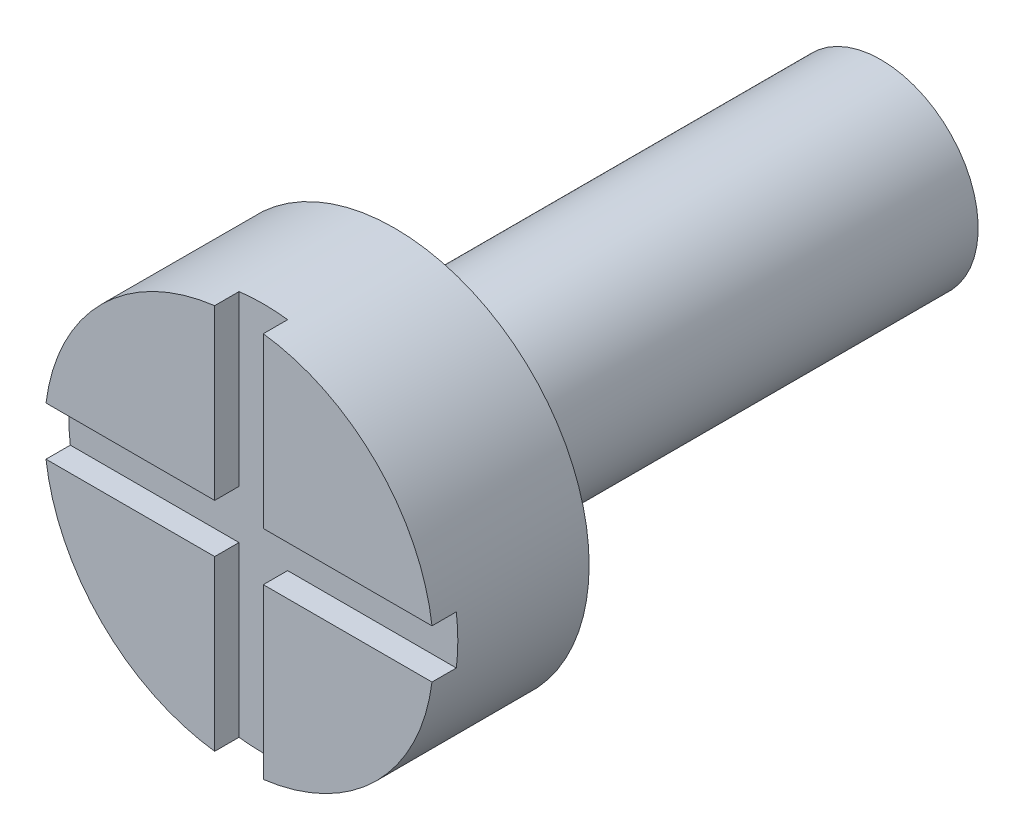
SolidWorks part; units mm, degrees
material "6061 Alloy"
ref_plane "Front Plane" through (0, 0, 0) normal (0, 0, 1) x (1, 0, 0)
ref_plane "Top Plane" through (0, 0, 0) normal (0, 1, 0) x (1, 0, 0)
ref_plane "Right Plane" through (0, 0, 0) normal (1, 0, 0) x (0, 0, -1)
sketch "Sketch1" plane through (0, 0, 0) normal (1, 0, 0) x (0, 0, -1)
  line L0 (0, 1) -> (0, 2)
  line L1 (0, 0) -> (5, 0) construction
  line L2 (5, 0) -> (5, 1)
  line L3 (5, 1) -> (0, 1)
  line L4 (0, 0) -> (-1.6, 0) construction
  line L5 (0, 2) -> (-1.6, 2)
  line L6 (-1.6, 2) -> (-1.6, 0)
  line L7 (5, 0) -> (-1.6, 0)
  dimension "D1" = 2
  dimension "D2" = 5
  dimension "D3" = 1
  dimension "D4" = 1.6
  dimension "D5" = 1.6
revolve "Revolve1" add sketch "Sketch1" angle 360 about L7
sketch "Sketch2" plane through (0, 0, 1.6) normal (0, 0, 1) x (1, 0, 0)
  line L0 (0, 0) -> (0, -0.25) construction
  line L2 (-2, -0.25) -> (-0.25, -0.25)
  line L3 (-0.25, 2) -> (-0.25, 0.25)
  line L4 (-2, 0.25) -> (-0.25, 0.25)
  line L5 (0.25, 2) -> (0.25, 0.25)
  line L6 (-0.25, 2) -> (0, 2.4802)
  line L7 (0, 2.4802) -> (0.25, 2)
  line L8 (2, 0.25) -> (2.3644, -0.1144)
  line L9 (2.3644, -0.1144) -> (2, -0.25)
  line L10 (0.25, -2) -> (0, -2.25)
  line L11 (0, -2.25) -> (-0.25, -2)
  line L12 (-2, 0.25) -> (-2.25, 0)
  line L13 (-2.25, 0) -> (-2, -0.25)
  line L14 (-2, -0.25) -> (-2.0176, -0.2309)
  line L15 (0, 2) -> (0, -2) construction
  line L16 (0.25, 0.25) -> (2, 0.25)
  line L18 (0.25, 0) -> (2, 0) construction
  line L20 (-0.25, -0.25) -> (-0.25, -2)
  line L21 (-0.25, 2) -> (-0.25, -2) construction
  line L22 (0.25, -0.25) -> (0.25, -2)
  line L23 (0.25, 2) -> (0.25, -2) construction
  line L24 (0.25, -0.25) -> (2, -0.25)
  dimension "D1" = 0.25
  dimension "D2" = 0.25
extrude "Cut-Extrude1" cut sketch "Sketch2" against normal blind 0.25
